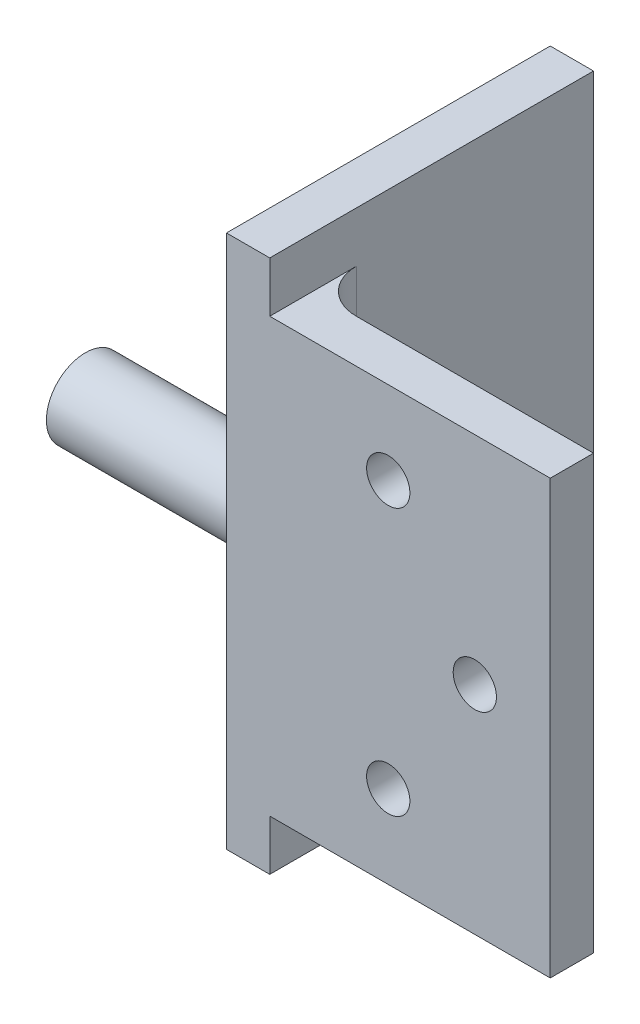
SolidWorks part; units mm, degrees
ref_plane "Front Plane" through (0, 0, 0) normal (0, 0, 1) x (1, 0, 0)
ref_plane "Top Plane" through (0, 0, 0) normal (0, 1, 0) x (1, 0, 0)
ref_plane "Right Plane" through (0, 0, 0) normal (1, 0, 0) x (0, 0, -1)
sketch "Sketch1" plane through (0, 0, 0) normal (0, 1, 0) x (1, 0, 0)
  line L0 (0, 0) -> (22.44, 0)
  line L1 (22.44, 0) -> (22.44, 3)
  line L2 (22.44, 3) -> (3, 3)
  line L3 (3, 3) -> (3, 22.44)
  line L4 (3, 22.44) -> (0, 22.44)
  line L5 (0, 22.44) -> (0, 0)
  dimension "D1" = 22.44
  dimension "D2" = 22.44
  dimension "D3" = 3
  dimension "D4" = 3
extrude "Boss-Extrude1" add sketch "Sketch1" along normal blind 37 contours L3 L4 L5 L0 L1 L2
fillet "Fillet1" radius 3 1 edges at (3, 18.5, -3)
sketch "Sketch2" plane through (0, 0, -22.44) normal (0, 0, -1) x (-1, 0, 0)
  line L0 (-22.44, 37) -> (-22.44, 0) construction
  line L1 (-3, 0) -> (-22.44, 0)
  line L2 (-3, 0) -> (-3, 3.5)
  line L3 (-3, 3.5) -> (-22.44, 3.5)
  line L4 (-22.44, 0) -> (-22.44, 3.5)
  line L6 (-3, 37) -> (-22.44, 37)
  line L7 (-3, 37) -> (-3, 33.5)
  line L8 (-3, 33.5) -> (-22.44, 33.5)
  line L9 (-22.44, 37) -> (-22.44, 33.5)
  circle A0 centre (-11.2128, 27.75) radius 1.5
  circle A1 centre (-17.2128, 18.5) radius 1.5
  circle A2 centre (-11.2128, 9.25) radius 1.5
  dimension "D8" = 3
  dimension "D1" = 3.5
  dimension "D2" = 3.5
  dimension "D3" = 18.5
  dimension "D4" = 9.25
  dimension "D5" = 9.25
  dimension "D6" = 9.25
  dimension "D7" = 6
extrude "Cut-Extrude1" cut sketch "Sketch2" against normal through all
sketch "Sketch3" plane through (0, 0, 0) normal (-1, 0, 0) x (0, 0, 1)
  line L0 (-22.44, 37) -> (0, 37) construction
  line L1 (-22.44, 37) -> (-22.44, 0) construction
  line L2 (-22.44, 0) -> (0, 0) construction
  line L3 (0, 37) -> (0, 0) construction
  circle A0 centre (-1.75, 35.25) radius 0.975
  circle A1 centre (-1.75, 1.75) radius 0.975
  circle A2 centre (-20.69, 1.75) radius 0.975
  circle A3 centre (-20.69, 35.25) radius 0.975
  circle A4 centre (-11.22, 11) radius 2.7
  dimension "D1" = 1.95
  dimension "D6" = 5.4
  dimension "D2" = 1.75
  dimension "D3" = 1.75
  dimension "D4" = 1.75
  dimension "D5" = 1.75
  dimension "D7" = 11.22
  dimension "D8" = 11.22
  dimension "D9" = 11
extrude "Boss-Extrude2" add sketch "Sketch3" along normal blind 21 contours A4
